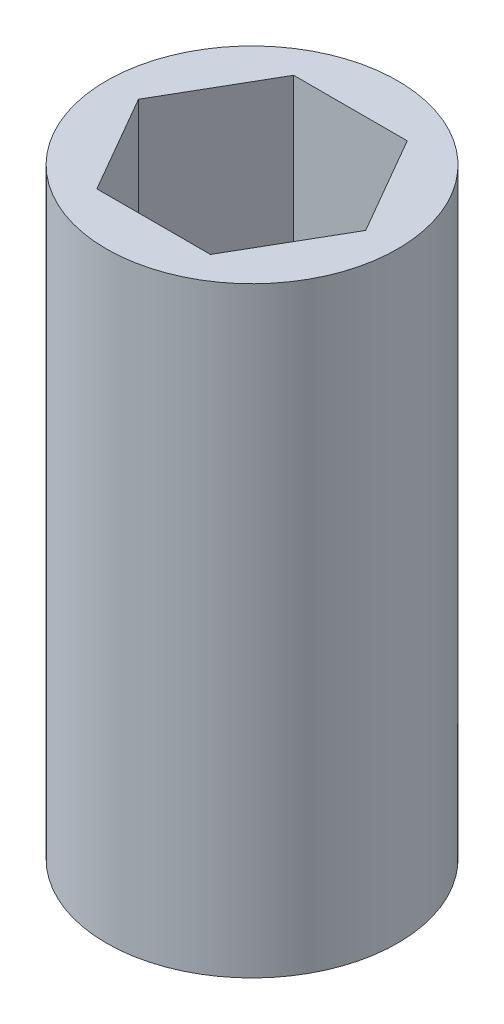
SolidWorks part; units mm, degrees
ref_plane "Front Plane" through (0, 0, 0) normal (0, 0, 1) x (1, 0, 0)
ref_plane "Top Plane" through (0, 0, 0) normal (0, 1, 0) x (1, 0, 0)
ref_plane "Right Plane" through (0, 0, 0) normal (1, 0, 0) x (0, 0, -1)
sketch "Sketch1" plane through (0, 0, 0) normal (0, 1, 0) x (1, 0, 0)
  line L1 (2.7863, -4.826) -> (5.5726, 0)
  line L2 (5.5726, 0) -> (2.7863, 4.826)
  line L3 (2.7863, 4.826) -> (-2.7863, 4.826)
  line L4 (-2.7863, 4.826) -> (-5.5726, 0)
  line L5 (-5.5726, 0) -> (-2.7863, -4.826)
  line L6 (-2.7863, -4.826) -> (2.7863, -4.826)
  circle A0 centre (0, 0) radius 7.1438
  circle A1 centre (0, 0) radius 4.826 construction
  dimension "D1" = 9.652
  dimension "D2" = 14.2875
extrude "Boss-Extrude1" add sketch "Sketch1" along normal mid plane 29.4894
